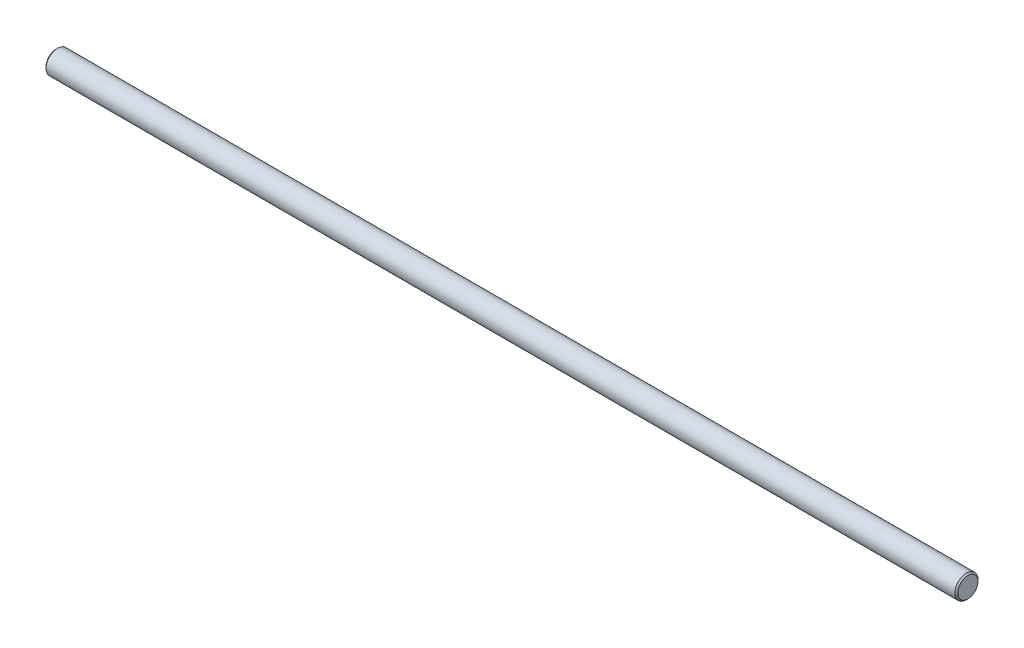
SolidWorks part; units mm, degrees
material "Chrome Stainless Steel"
ref_plane "Front Plane" through (0, 0, 0) normal (0, 0, 1) x (1, 0, 0)
ref_plane "Top Plane" through (0, 0, 0) normal (0, 1, 0) x (1, 0, 0)
ref_plane "Right Plane" through (0, 0, 0) normal (1, 0, 0) x (0, 0, -1)
sketch "Sketch1" plane through (0, 0, 0) normal (0, 0, 1) x (1, 0, 0)
  line L0 (0, 3.5) -> (0, 0)
  line L1 (0, 0) -> (315, 0)
  line L2 (315, 0) -> (315, 3.5)
  line L3 (315, 3.5) -> (314.5, 4)
  line L4 (314.5, 4) -> (0.5, 4)
  line L5 (0.5, 4) -> (0, 3.5)
  line L6 (0, 0) -> (315, 0) construction
revolve "Revolve1" add sketch "Sketch1" angle 360 about L6
